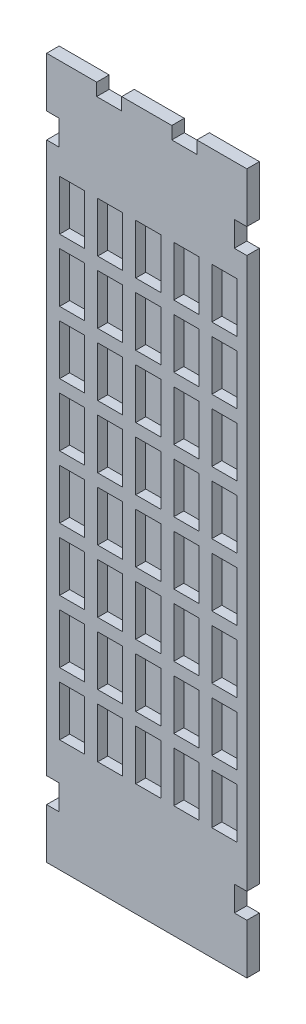
SolidWorks part; units mm, degrees
ref_plane "Front Plane" through (0, 0, 0) normal (0, 0, 1) x (1, 0, 0)
ref_plane "Top Plane" through (0, 0, 0) normal (0, 1, 0) x (1, 0, 0)
ref_plane "Right Plane" through (0, 0, 0) normal (1, 0, 0) x (0, 0, -1)
sketch "Sketch1" plane through (0, 0, 0) normal (0, 0, 1) x (1, 0, 0)
  line L0 (12.7, -177.8) -> (38.1, -177.8)
  line L1 (0, 0) -> (50.8, 0)
  line L2 (0, 0) -> (0, -177.8)
  line L3 (0, -177.8) -> (12.7, -177.8)
  line L4 (50.8, 0) -> (50.8, -177.8)
  line L5 (12.7, 0) -> (19.05, 0)
  line L6 (12.7, 0) -> (12.7, -3.175)
  line L7 (12.7, -3.175) -> (19.05, -3.175)
  line L8 (19.05, 0) -> (19.05, -3.175)
  line L9 (31.75, 0) -> (38.1, 0)
  line L10 (31.75, 0) -> (31.75, -3.175)
  line L11 (31.75, -3.175) -> (38.1, -3.175)
  line L12 (38.1, 0) -> (38.1, -3.175)
  line L13 (50.8, -12.7) -> (47.625, -12.7)
  line L14 (50.8, -12.7) -> (50.8, -19.05)
  line L15 (50.8, -19.05) -> (47.625, -19.05)
  line L16 (47.625, -12.7) -> (47.625, -19.05)
  line L17 (50.8, -158.75) -> (47.625, -158.75)
  line L18 (50.8, -158.75) -> (50.8, -165.1)
  line L19 (50.8, -165.1) -> (47.625, -165.1)
  line L20 (47.625, -158.75) -> (47.625, -165.1)
  line L25 (38.1, -177.8) -> (50.8, -177.8)
  line L29 (0, -165.1) -> (3.175, -165.1)
  line L30 (0, -165.1) -> (0, -158.75)
  line L31 (0, -158.75) -> (3.175, -158.75)
  line L32 (3.175, -165.1) -> (3.175, -158.75)
  line L33 (0, -19.05) -> (3.175, -19.05)
  line L34 (0, -19.05) -> (0, -12.7)
  line L35 (0, -12.7) -> (3.175, -12.7)
  line L36 (3.175, -19.05) -> (3.175, -12.7)
  dimension "D1" = 50.8
  dimension "D2" = 177.8
  dimension "D3" = 12.7
  dimension "D4" = 6.35
  dimension "D5" = 3.175
  dimension "D6" = 6.35
  dimension "D7" = 3.175
  dimension "D8" = 12.7
  dimension "D9" = 12.7
  dimension "D10" = 6.35
  dimension "D11" = 3.175
  dimension "D12" = 3.175
  dimension "D13" = 6.35
  dimension "D14" = 12.7
  dimension "D21" = 3.175
  dimension "D22" = 6.35
  dimension "D23" = 12.7
  dimension "D24" = 12.7
  dimension "D25" = 6.35
  dimension "D26" = 3.175
extrude "Boss-Extrude1" add sketch "Sketch1" along normal blind 3.175
sketch "Sketch2" plane through (0, 0, 3.175) normal (0, 0, 1) x (1, 0, 0)
  line L0 (0, -19.05) -> (3.175, -19.05) construction
  line L1 (3.302, -25.4) -> (9.652, -25.4)
  line L2 (3.302, -25.4) -> (3.302, -38.1)
  line L3 (3.302, -38.1) -> (9.652, -38.1)
  line L4 (9.652, -25.4) -> (9.652, -38.1)
  line L5 (3.302, -25.4) -> (9.652, -38.1) construction
  line L6 (3.302, -38.1) -> (9.652, -25.4) construction
  line L7 (0, -19.05) -> (0, -158.75) construction
  point P0 (6.477, -31.75)
  dimension "D1" = 6.35
  dimension "D2" = 12.7
  dimension "D3" = 6.35
  dimension "D4" = 3.302
extrude "Cut-Extrude1" cut sketch "Sketch2" against normal blind 2.54
pattern_linear "LPattern1" count 5 spacing 9.652 along (1, 0, 0) count 8 spacing 15.875 along (0, -1, 0) of "Cut-Extrude1"
